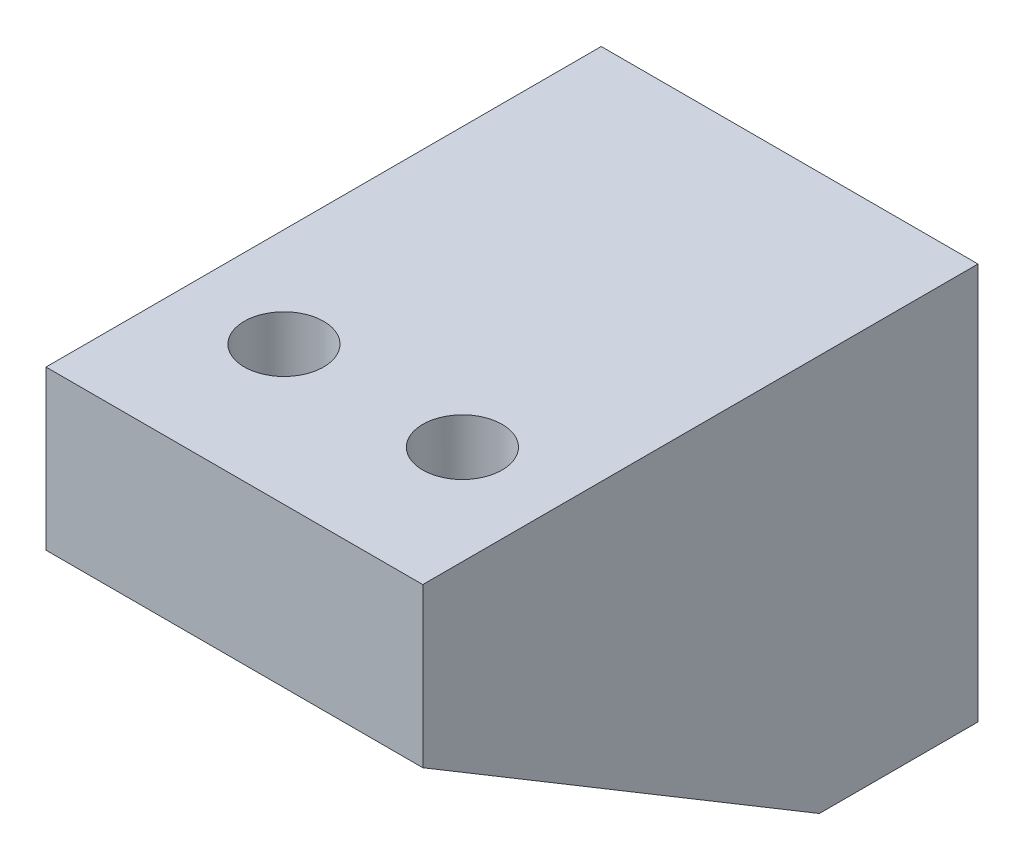
SolidWorks part; units mm, degrees
ref_plane "Front Plane" through (0, 0, 0) normal (0, 0, 1) x (1, 0, 0)
ref_plane "Top Plane" through (0, 0, 0) normal (0, 1, 0) x (1, 0, 0)
ref_plane "Right Plane" through (0, 0, 0) normal (1, 0, 0) x (0, 0, -1)
sketch "Sketch1" plane through (0, 0, 0) normal (0, 0, 1) x (1, 0, 0)
  line L1 (-12.6343, 16.1799) -> (6.3657, 16.1799)
  line L2 (-12.6343, 16.1799) -> (-12.6343, -3.8201)
  line L3 (-12.6343, -3.8201) -> (6.3657, -3.8201)
  line L4 (6.3657, 16.1799) -> (6.3657, -3.8201)
  dimension "D1" = 19
  dimension "D2" = 20
extrude "Boss-Extrude1" add sketch "Sketch1" along normal blind 8
sketch "Sketch2" plane through (0, 0, 8) normal (0, 0, 1) x (1, 0, 0)
  line L0 (6.3657, -3.8201) -> (6.3657, 16.1799) construction
  line L1 (-12.6343, 16.1799) -> (6.3657, 16.1799)
  line L2 (-12.6343, 16.1799) -> (-12.6343, 8.1799)
  line L3 (-12.6343, 8.1799) -> (6.3657, 8.1799)
  line L4 (6.3657, 16.1799) -> (6.3657, 8.1799)
  dimension "D1" = 8
extrude "Boss-Extrude2" add sketch "Sketch2" along normal blind 20
sketch "Sketch3" plane through (0, 0, 8) normal (0, 0, 1) x (1, 0, 0)
  line L0 (-12.6343, -3.8201) -> (6.3657, -3.8201) construction
  line L1 (-12.6343, 8.1799) -> (-12.6343, -3.8201) construction
  line L2 (6.3657, -3.8201) -> (6.3657, 8.1799) construction
  circle A0 centre (-8.6343, 1.1799) radius 2
  circle A1 centre (2.3657, 1.1799) radius 2
  dimension "D1" = 4
  dimension "D2" = 4
  dimension "D3" = 0
  dimension "D4" = 5
  dimension "D5" = 4
  dimension "D6" = 4
extrude "Cut-Extrude1" cut sketch "Sketch3" against normal blind 20
sketch "Sketch4" plane through (0, 8.1799, 0) normal (0, -1, 0) x (1, 0, 0)
  line L0 (-12.6343, 28) -> (6.3657, 28) construction
  line L1 (-12.6343, 28) -> (-12.6343, 8) construction
  line L2 (6.3657, 28) -> (6.3657, 8) construction
  circle A0 centre (-7.6343, 21) radius 2
  circle A1 centre (1.3657, 21) radius 2
  dimension "D1" = 4
  dimension "D2" = 4
  dimension "D3" = 0
  dimension "D4" = 7
  dimension "D5" = 5
  dimension "D6" = 5
extrude "Cut-Extrude2" cut sketch "Sketch4" against normal blind 20
sketch "Sketch5" plane through (-12.6343, 0, 0) normal (-1, 0, 0) x (0, 0, 1)
  line L0 (28, 8.1799) -> (8, -3.8201)
  line L1 (8, -3.8201) -> (8, 8.1799)
  line L2 (8, 8.1799) -> (28, 8.1799)
extrude "Boss-Extrude3" add sketch "Sketch5" against normal up to vertex (19 mm away)
sketch "Sketch7" plane through (0, 8.1799, 0) normal (0, 1, 0) x (1, 0, 0)
  circle A1 centre (1.3657, -21) radius 3.5
  circle A2 centre (-7.6343, -21) radius 3.5
  dimension "D1" = 7
  dimension "D2" = 7
extrude "Cut-Extrude3" cut sketch "Sketch7" against normal blind 20
sketch "Sketch8" plane through (0, 0, 8) normal (0, 0, -1) x (-1, 0, 0)
  circle A0 centre (8.6343, 1.1799) radius 3.5
  circle A1 centre (-2.3657, 1.1799) radius 3.5
  dimension "D1" = 7
  dimension "D2" = 7
extrude "Cut-Extrude4" cut sketch "Sketch8" against normal blind 20
